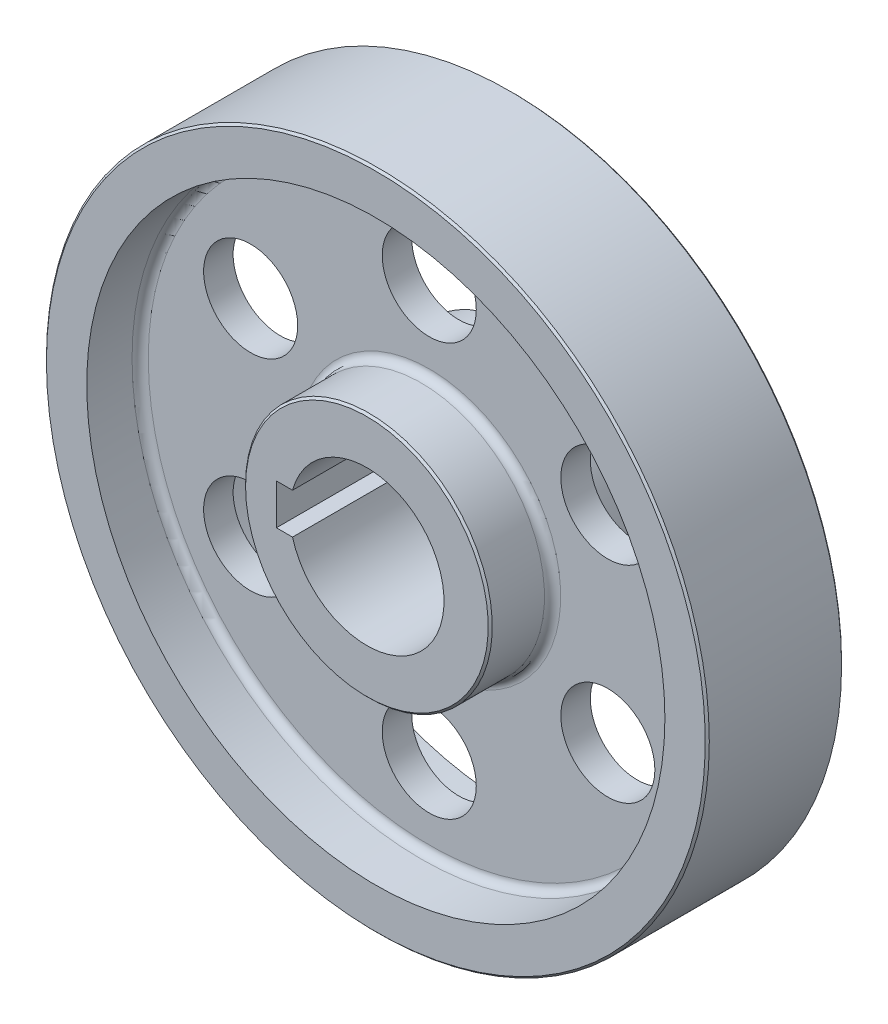
SolidWorks part; units mm, degrees
ref_plane "Front Plane" through (0, 0, 0) normal (0, 0, 1) x (1, 0, 0)
ref_plane "Top Plane" through (0, 0, 0) normal (0, 1, 0) x (1, 0, 0)
ref_plane "Right Plane" through (0, 0, 0) normal (1, 0, 0) x (0, 0, -1)
sketch "Sketch1" plane through (0, 0, 0) normal (1, 0, 0) x (0, 0, -1)
  line L0 (-17.4141, 0) -> (20.5859, 0) construction
  line L1 (-17.4141, 19) -> (20.5859, 19)
  line L2 (20.5859, 19) -> (20.5859, 30.4)
  line L5 (18.3859, 81.6785) -> (-15.2141, 81.6785)
  line L6 (-15.2141, 81.6785) -> (-15.2141, 71.2378)
  line L8 (-17.4141, 30.4) -> (-17.4141, 19)
  line L9 (-15.2141, 50.8189) -> (18.3859, 50.8189) construction
  line L10 (-15.2141, 71.2378) -> (-2.0495, 71.2378)
  line L11 (-2.0495, 71.2378) -> (-2.0495, 30.4)
  line L12 (-2.0495, 30.4) -> (-17.4141, 30.4)
  line L13 (5.2213, 30.4) -> (20.5859, 30.4)
  line L14 (1.5859, 81.6785) -> (1.5859, 0) construction
  line L15 (5.2213, 71.2378) -> (18.3859, 71.2378)
  line L16 (5.2213, 71.2378) -> (5.2213, 30.4)
  line L17 (18.3859, 71.2378) -> (18.3859, 81.6785)
  dimension "D1" = 33.6
  dimension "D2" = 38
  dimension "D3" = 30.4
  dimension "D4" = 19
  dimension "D5" = 81.6785
  dimension "D6" = 50.8189
  dimension "D7" = 71.2378
  dimension "D8" = 7.2708
revolve "Revolve1" add sketch "Sketch1" angle 360 about L0
sketch "Sketch2" plane through (0, 0, 2.0495) normal (0, 0, 1) x (1, 0, 0)
  circle A0 centre (0, 50.8189) radius 11.5892
  circle A1 centre (44.0104, 25.4094) radius 11.5892
  circle A2 centre (44.0104, -25.4094) radius 11.5892
  circle A3 centre (0, -50.8189) radius 11.5892
  circle A4 centre (-44.0104, -25.4094) radius 11.5892
  circle A5 centre (-44.0104, 25.4094) radius 11.5892
  point P16 (0, 0)
  dimension "D2" = 23.1784
  dimension "D1" = 50.8189
  dimension "D3" = 6
extrude "Cut-Extrude1" cut sketch "Sketch2" against normal up to next
fillet "Fillet1" radius 2 4 edges at (30.4, 0, -5.2213) (30.4, 0, 2.0495) (71.2378, 0, -5.2213) (71.2378, 0, 2.0495)
sketch "Sketch4" plane through (0, 0, 17.4141) normal (0, 0, 1) x (1, 0, 0)
  line L0 (-22.3, 5) -> (-22.3, -5)
  line L1 (-22.3, 0) -> (-19, 0) construction
  line L2 (-22.3, 5) -> (-18.3303, 5)
  line L3 (-22.3, -5) -> (-18.3303, -5)
  circle A0 centre (0, 0) radius 19 construction
  arc A1 (-18.3303, 5) -> (-18.3303, -5) centre (0, 0) ccw
  dimension "D1" = 10
  dimension "D2" = 3.3
extrude "Cut-Extrude3" cut sketch "Sketch4" against normal up to next
chamfer "Chamfer1" distance 0.5 angle 45 4 edges at (30.4, 0, -20.5859) (30.4, 0, 17.4141) (81.6785, 0, 15.2141) (81.6785, 0, -18.3859)
sketch "dw2" plane through (0, 0, 15.2141) normal (0, 0, 1) x (1, 0, 0)
  circle A0 centre (0, 0) radius 80.1468
  dimension "D1" = 160.2936
sketch "df2" plane through (0, 0, -18.3859) normal (0, 0, -1) x (-1, 0, 0)
  circle A0 centre (0, 0) radius 77.2967
  dimension "D1" = 154.5934
